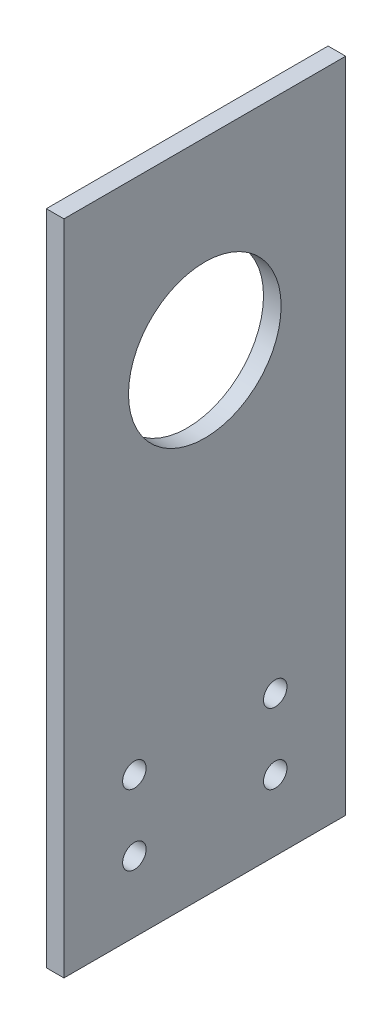
SolidWorks part; units mm, degrees
material "6061 Alloy"
ref_plane "Front Plane" through (0, 0, 0) normal (0, 0, 1) x (1, 0, 0)
ref_plane "Top Plane" through (0, 0, 0) normal (0, 1, 0) x (1, 0, 0)
ref_plane "Right Plane" through (0, 0, 0) normal (1, 0, 0) x (0, 0, -1)
sketch "Sketch1" plane through (0, 0, 0) normal (1, 0, 0) x (0, 0, -1)
  line L1 (-38.1, 88.9) -> (38.1, 88.9)
  line L2 (-38.1, 88.9) -> (-38.1, -88.9)
  line L3 (-38.1, -88.9) -> (38.1, -88.9)
  line L4 (38.1, 88.9) -> (38.1, -88.9)
  line L5 (-38.1, 88.9) -> (38.1, -88.9) construction
  line L6 (-38.1, -88.9) -> (38.1, 88.9) construction
  point P0 (0, 0)
  dimension "D1" = 177.8
  dimension "D2" = 76.2
extrude "Boss-Extrude1" add sketch "Sketch1" along normal blind 4.7625
sketch "Sketch2" plane through (4.7625, 0, 0) normal (1, 0, 0) x (0, 0, -1)
  line L0 (-38.1, -88.9) -> (38.1, -88.9) construction
  line L1 (-38.1, 88.9) -> (-38.1, -88.9) construction
  circle A0 centre (0, 39.116) radius 20.6375
  dimension "D1" = 128.016
  dimension "D2" = 38.1
  dimension "D3" = 41.275
extrude "Cut-Extrude1" cut sketch "Sketch2" against normal up to next
sketch "Sketch4" plane through (4.7625, 0, 0) normal (1, 0, 0) x (0, 0, -1)
  line L0 (-38.1, 88.9) -> (-38.1, -88.9) construction
  line L1 (-38.1, -88.9) -> (38.1, -88.9) construction
  circle A0 centre (-19.05, -50.8) radius 3.175
  circle A1 centre (19.05, -50.8) radius 3.175
  circle A2 centre (19.05, -69.85) radius 3.175
  circle A3 centre (-19.05, -69.85) radius 3.175
  dimension "D1" = 19.05
  dimension "D2" = 6.35
  dimension "D3" = 38.1
  dimension "D5" = 2
  dimension "D4" = 2
extrude "Cut-Extrude2" cut sketch "Sketch4" against normal up to next
